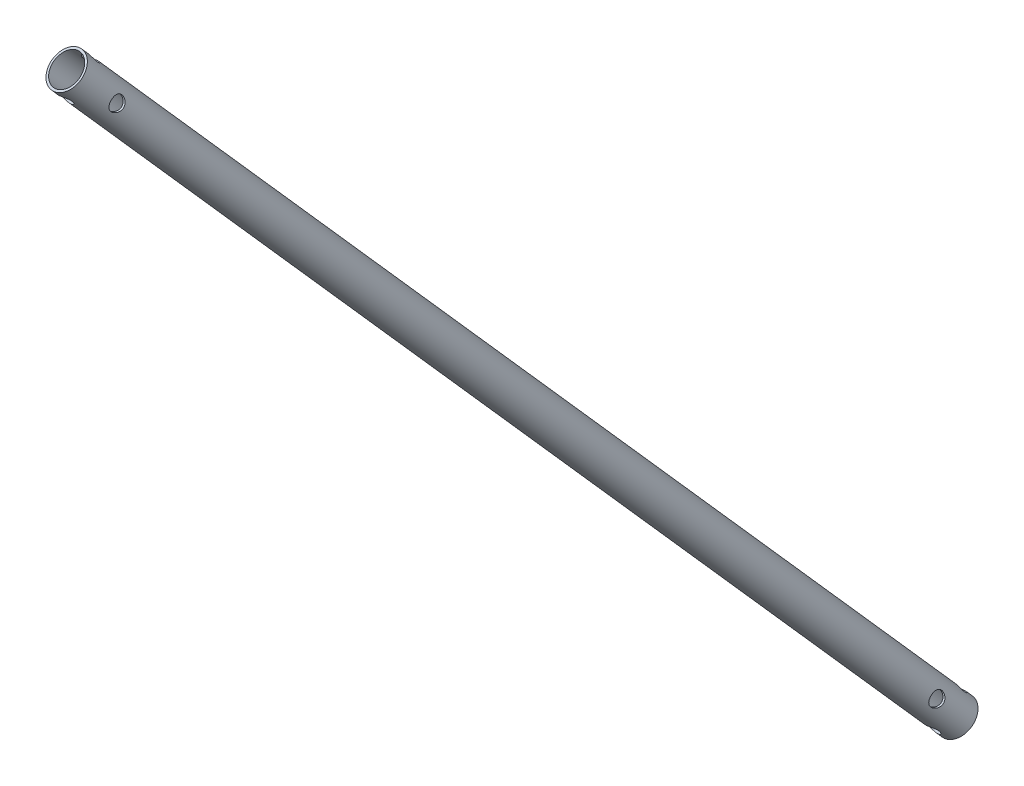
SolidWorks part; units mm, degrees
ref_plane "Front Plane" through (0, 0, 0) normal (0, 0, 1) x (1, 0, 0)
ref_plane "Top Plane" through (0, 0, 0) normal (0, 1, 0) x (1, 0, 0)
ref_plane "Right Plane" through (0, 0, 0) normal (1, 0, 0) x (0, 0, -1)
sketch3d "3DSketch1"
  line L0 (158.525, 944.5982, -852.9961) -> (302.8955, 382.0075, -1334.7726)
other "Pipe 25.4 X 1.6(1)"
ref_plane "Plane1" through (158.525, 944.5982, -852.9961) normal (0.1913, -0.7455, -0.6384) x (0.8988, 0.3945, -0.1913)
sketch "Sketch11" plane through (158.525, 944.5982, -852.9961) normal (0.1913, -0.7455, -0.6384) x (0.8988, 0.3945, -0.1913)
  circle A0 centre (0, 0) radius 11.1
  circle A1 centre (0, 0) radius 12.7
  point P3 (0, 0)
  dimension "Out_dia" = 25.4
  dimension "D1" = 1.6
ref_plane "Plane2" through (0, 821.0611, -958.7875) normal (0, -0.6504, 0.7596) x (0.1913, -0.7455, -0.6384)
sketch "Sketch12" plane through (0, 821.0611, -958.7875) normal (0, -0.6504, 0.7596) x (0.1913, -0.7455, -0.6384)
  line L0 (-129.3122, 186.713) -> (625.3133, 186.713) construction
  circle A0 centre (615.3133, 186.713) radius 5
  circle A1 centre (-119.3122, 186.713) radius 5
  dimension "D1" = 10
  dimension "D2" = 10
  dimension "D3" = 10
extrude "Cut-Extrude1" cut sketch "Sketch12" against normal mid plane 40
ref_plane "Plane3" through (183.2642, 27.1319, 23.2345) normal (-0.9815, -0.1453, -0.1244) x (0.1913, -0.7455, -0.6384)
sketch "Sketch13" plane through (183.2642, 27.1319, 23.2345) normal (-0.9815, -0.1453, -0.1244) x (0.1913, -0.7455, -0.6384)
  line L0 (-129.3122, -1262.3053) -> (625.3133, -1262.3053) construction
  circle A0 centre (595.3133, -1262.3053) radius 5
  circle A1 centre (-99.3122, -1262.3053) radius 5
  point P0 (585.3133, -1262.3053)
  point P1 (-89.3122, -1262.3053)
  dimension "D3" = 10
  dimension "D1" = 40
  dimension "D2" = 40
  dimension "D4" = 10
  dimension "D5" = 10
extrude "Cut-Extrude2" cut sketch "Sketch13" against normal mid plane 40
